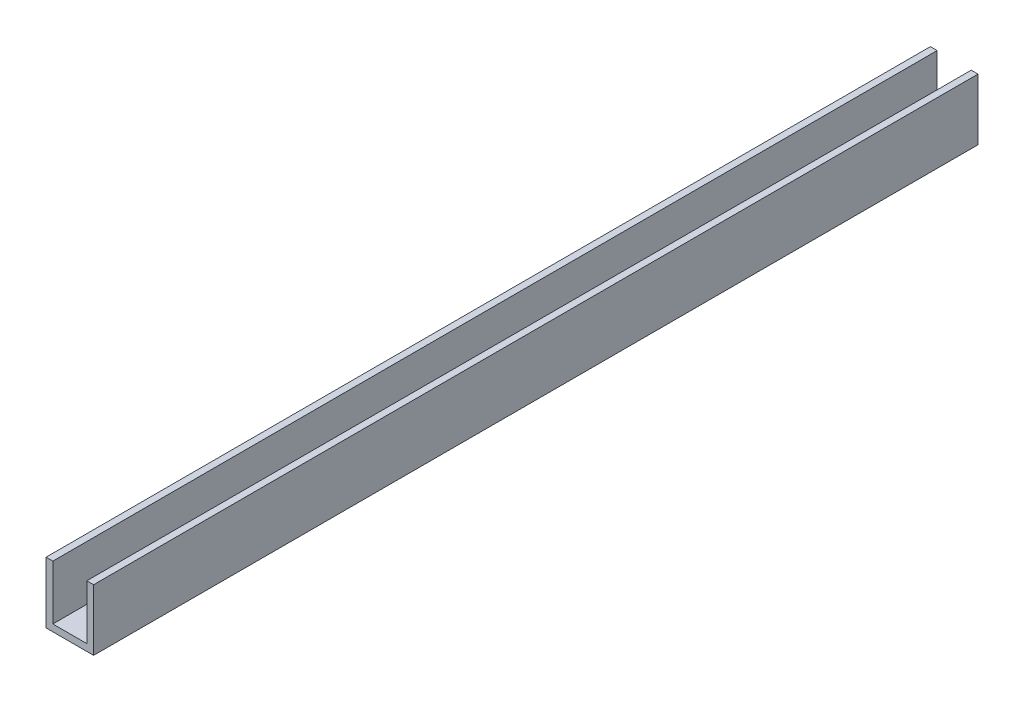
SolidWorks part; units mm, degrees
ref_plane "Front Plane" through (0, 0, 0) normal (0, 0, 1) x (1, 0, 0)
ref_plane "Top Plane" through (0, 0, 0) normal (0, 1, 0) x (1, 0, 0)
ref_plane "Right Plane" through (0, 0, 0) normal (1, 0, 0) x (0, 0, -1)
sketch "Sketch2" plane through (0, 0, 0) normal (0, 0, 1) x (1, 0, 0)
  line L0 (-3.5, 0) -> (3.5, 0)
  line L1 (3.5, 0) -> (3.5, 9)
  line L2 (3.5, 9) -> (2.5, 9)
  line L3 (2.5, 9) -> (2.5, 1)
  line L4 (2.5, 1) -> (-2.5, 1)
  line L5 (-2.5, 9) -> (-2.5, 1)
  line L6 (-3.5, 9) -> (-2.5, 9)
  line L7 (-3.5, 0) -> (-3.5, 9)
  point P6 (0, 1)
  point P9 (0, 0)
  point P10 (0, 0)
  point P11 (0, 0)
  dimension "D1" = 9
  dimension "D2" = 1
  dimension "D3" = 5
  dimension "D4" = 1
extrude "Boss-Extrude2" add sketch "Sketch2" along normal blind 130
